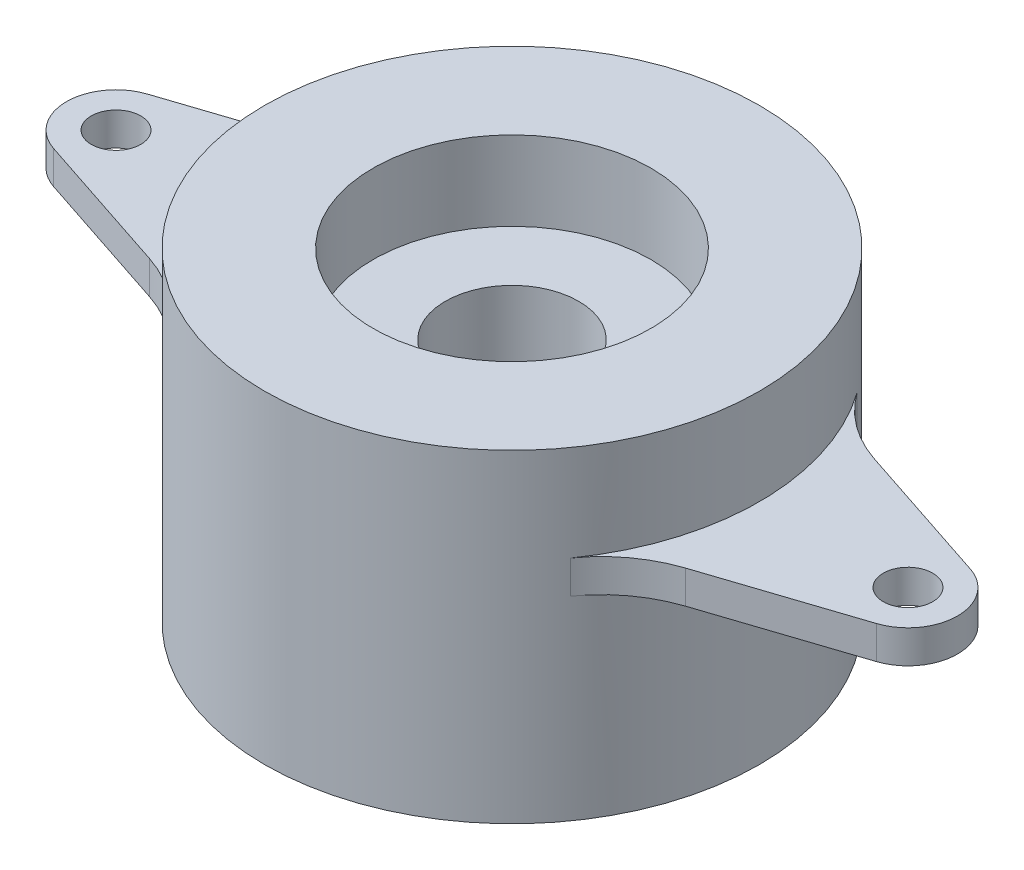
SolidWorks part; units mm, degrees
material "1060 Alloy"
ref_plane "Front Plane" through (0, 0, 0) normal (0, 0, 1) x (1, 0, 0)
ref_plane "Top Plane" through (0, 0, 0) normal (0, 1, 0) x (1, 0, 0)
ref_plane "Right Plane" through (0, 0, 0) normal (1, 0, 0) x (0, 0, -1)
sketch "Sketch1" plane through (0, 0, 0) normal (0, 0, 1) x (1, 0, 0)
  line L0 (21.05, 24.5) -> (37.5, 24.5)
  line L1 (21.05, 24.5) -> (21.05, 12.5)
  line L2 (21.05, 12.5) -> (10.1, 12.5)
  line L3 (10.1, 12.5) -> (10.1, -12.5)
  line L4 (37.5, 24.5) -> (37.5, -24.5)
  line L5 (37.5, -24.5) -> (21.05, -24.5)
  line L6 (21.05, -24.5) -> (21.05, -12.5)
  line L7 (21.05, -12.5) -> (10.1, -12.5)
  line L8 (0, 0) -> (0, 21.563) construction
  point P11 (10.1, 0)
  dimension "D1" = 12
  dimension "D2" = 12
  dimension "D3" = 21.05
  dimension "D4" = 10.1
  dimension "D5" = 25
  dimension "D6" = 37.5
revolve "Revolve1" add sketch "Sketch1" angle 360 about L8
sketch "Sketch2" plane through (0, 0, 0) normal (0, 1, 0) x (1, 0, 0)
  line L0 (-60, 0) -> (60, 0) construction
  line L1 (-62.3542, 7.1209) -> (-40.5957, 14.3143)
  line L2 (-62.3542, -7.1209) -> (-40.5957, -14.3143)
  line L3 (-30.5697, 21.7196) -> (-30.5697, -21.7196)
  line L4 (0, -37.5) -> (0, 37.5) construction
  line L5 (30.5697, 21.7196) -> (30.5697, -21.7196)
  line L6 (62.3542, -7.1209) -> (40.5957, -14.3143)
  line L7 (62.3542, 7.1209) -> (40.5957, 14.3143)
  circle A0 centre (-60, 0) radius 3.75
  arc A1 (-62.3542, 7.1209) -> (-62.3542, -7.1209) centre (-60, 0) ccw
  circle A2 centre (0, 0) radius 37.5 construction
  arc A3 (-30.5697, -21.7196) -> (-30.5697, 21.7196) centre (0, 0) ccw construction
  arc A4 (-40.5957, -14.3143) -> (-30.5697, -21.7196) centre (-46.8735, -33.3035) cw
  arc A5 (-40.5957, 14.3143) -> (-30.5697, 21.7196) centre (-46.8735, 33.3035) ccw
  arc A6 (40.5957, 14.3143) -> (30.5697, 21.7196) centre (46.8735, 33.3035) cw
  arc A7 (40.5957, -14.3143) -> (30.5697, -21.7196) centre (46.8735, -33.3035) ccw
  arc A8 (62.3542, 7.1209) -> (62.3542, -7.1209) centre (60, 0) cw
  circle A9 centre (60, 0) radius 3.75
  point P12 (0, 0)
  point P15 (-33.6148, -16.6222)
  point P18 (-33.6148, 16.6222)
  point P21 (0, 0)
  dimension "D1" = 15
  dimension "D2" = 7.5
  dimension "D3" = 120
  dimension "D4" = 20
extrude "Boss-Extrude1" add sketch "Sketch2" along normal blind 5 from offset 5
sketch "Sketch3" plane through (0, 0, 0) normal (1, 0, 0) x (0, 0, -1)
  line L0 (-37.5, 0) -> (37.5, 0)
  line L1 (37.5, -24.5) -> (37.5, 24.5) construction
  line L2 (-37.5, 24.5) -> (-37.5, -24.5) construction
sketch "Sketch4" plane through (0, 24.5, 0) normal (0, 1, 0) x (1, 0, 0)
  line L0 (-67.5, 0) -> (67.5, 0)
  arc A0 (-62.3542, 7.1209) -> (-62.3542, -7.1209) centre (-60, 0) ccw construction
  arc A1 (62.3542, -7.1209) -> (62.3542, 7.1209) centre (60, 0) ccw construction
